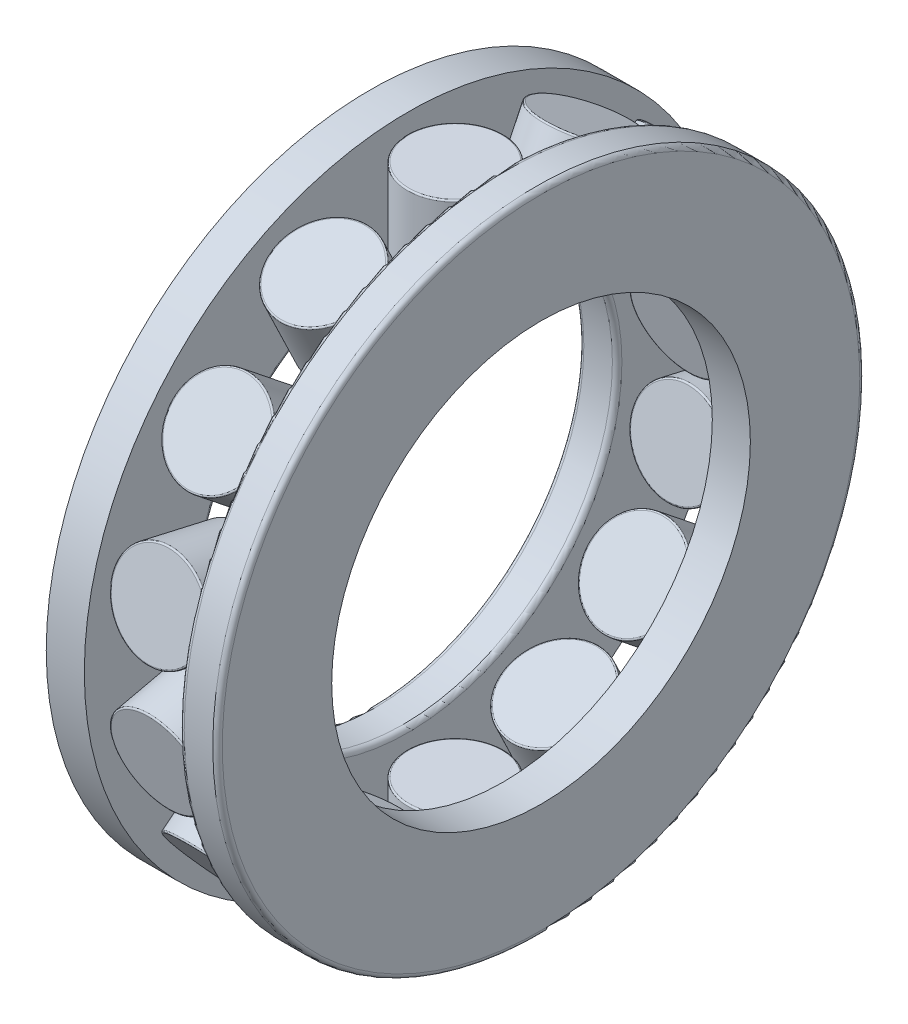
SolidWorks part; units mm, degrees
ref_plane "Plane1" through (0, 0, 0) normal (0, 0, 1) x (1, 0, 0)
ref_plane "Plane2" through (0, 0, 0) normal (0, 1, 0) x (1, 0, 0)
ref_plane "Plane3" through (0, 0, 0) normal (1, 0, 0) x (0, 0, -1)
sketch "Clipboard" plane through (0, 0, 0) normal (0, 0, 1) x (1, 0, 0)
  line L0 (-10, 0) -> (10, 0) construction
  line L1 (0, 0) -> (21.6965, -5.4095)
  line L2 (0, 0) -> (27.3662, 35.0271)
  line L3 (0, 0) -> (13.7666, -17.6205)
  line L4 (0, 0) -> (-22.3471, -0.7804)
  dimension "BallCLRad" = 44.45
  dimension "Count" = 52
  dimension "Show_count" = 52
  dimension "Max_count" = 14
  dimension "Min_count" = 2
sketch "InnRacSke" plane through (0, 0, 0) normal (0, 0, 1) x (1, 0, 0)
  line L1 (-7.9375, 34.925) -> (-14.2875, 34.925)
  line L2 (-14.2875, 34.925) -> (-14.2875, 53.975)
  line L3 (-14.2875, 53.975) -> (-7.9375, 53.975)
  line L4 (-7.9375, 53.975) -> (-7.9375, 34.925)
  line L5 (-34.925, 0) -> (34.925, 0) construction
  line L6 (0, 0) -> (0, 25.4) construction
  dimension "ID" = 69.85
  dimension "OD" = 107.95
  dimension "Width" = 28.575
  dimension "gap" = 15.875
revolve "Race" add sketch "InnRacSke" angle 360 about L5
ref_axis "Axis1" through (-50, 0, 0) along (1, 0, 0)
sketch "RolDetSke" plane through (0, 0, 0) normal (0, 0, 1) x (1, 0, 0)
  line L0 (0, 33.02) -> (0, 55.88) construction
  line L3 (0, 50.8) -> (7.7232, 50.8)
  line L4 (0, 50.8) -> (0, 38.1)
  line L5 (0, 38.1) -> (7.7232, 38.1)
  line L6 (7.9772, 50.546) -> (7.9772, 38.354)
  arc A0 (7.9772, 38.354) -> (7.7232, 38.1) centre (7.7232, 38.354) cw
  arc A1 (7.7232, 50.8) -> (7.9772, 50.546) centre (7.7232, 50.546) cw
  dimension "D1" = 0.254
  dimension "Roller_diameter" = 15.9544
  dimension "Cyl_Len" = 12.7
  dimension "offset" = 38.1
revolve "RollerDetailed" add sketch "RolDetSke" angle 360 about L0
sketch "RolSimSke" plane through (0, 0, 0) normal (0, 0, 1) x (1, 0, 0)
  line L1 (-17.78, 0) -> (12.7, 0) construction
  line L3 (-7.7232, 50.8) -> (7.7232, 50.8)
  line L4 (-7.9772, 50.546) -> (-7.9772, 38.354)
  line L5 (-7.7232, 38.1) -> (7.7232, 38.1)
  line L6 (7.9772, 50.546) -> (7.9772, 38.354)
  arc A0 (-7.9772, 38.354) -> (-7.7232, 38.1) centre (-7.7232, 38.354) ccw
  arc A1 (-7.7232, 50.8) -> (-7.9772, 50.546) centre (-7.7232, 50.546) ccw
  arc A2 (7.9772, 50.546) -> (7.7232, 50.8) centre (7.7232, 50.546) ccw
  arc A3 (7.7232, 38.1) -> (7.9772, 38.354) centre (7.7232, 38.354) ccw
  dimension "Roller_diameter" = 15.9544
  dimension "Cyl_Len" = 12.7
  dimension "offset" = 38.1
  dimension "Rol_rad" = 0.254
  dimension "Halfdia" = 7.9772
revolve "RollersSimplified" [suppressed] add sketch "RolSimSke" angle 360 about L1
mirror "Mirror1" about plane through (0, 0, 0) normal (1, 0, 0) of "Race"
fillet "Fillet" radius 0.7937 4 edges at (14.2875, 0, -53.975) (7.9375, 0, -53.975) (-14.2875, 0, -34.925) (-7.9375, 0, -34.925)
pattern_circular "RollersDetailed" count 14 every 25.714 about axis through (-50, 0, 0) along (1, 0, 0) of "RollerDetailed"
sketch "CagSpiSke" plane through (0, 0, 0) normal (0, 0, 1) x (1, 0, 0)
  line L0 (2.3932, 35.6235) -> (2.3932, 52.8955)
  line L1 (2.3932, 52.8955) -> (-2.3932, 52.8955)
  line L2 (-2.3932, 35.6235) -> (-2.3932, 52.8955)
  line L3 (-2.3932, 35.6235) -> (2.3932, 35.6235)
  line L4 (-34.925, 0) -> (34.925, 0) construction
  line L5 (0, 0) -> (0, 55.5677) construction
  dimension "ID" = 71.247
  dimension "OD" = 105.791
  dimension "Thickness" = 4.7863
revolve "CageSpine" [suppressed] add sketch "CagSpiSke" angle 360 about L4
equation "\"BallCLRad@Clipboard\" =  ( \"OD@InnRacSke\" + \"ID@InnRacSke\" )  / 4"
equation "\"offset@RolDetSke\" = \"BallCLRad@Clipboard\" - \"Cyl_Len@RolDetSke\" / 2"
equation "\"Roller_diameter@RolDetSke\" = \"gap@InnRacSke\" * 1.005"
equation "\"Cyl_Len@RolSimSke\" = \"Cyl_Len@RolDetSke\""
equation "\"offset@RolSimSke\" = \"BallCLRad@Clipboard\" - \"Cyl_Len@RolSimSke\" / 2"
equation "\"Roller_diameter@RolSimSke\" = \"Roller_diameter@RolDetSke\""
equation "\"Halfdia@RolSimSke\" = \"Roller_diameter@RolSimSke\" / 2"
equation "\"Max_count@Clipboard\" = int( 3.14159265 / atn(( \"Roller_diameter@RolDetSke\" / 2) / sqr( \"offset@RolDetSke\"  *  \"offset@RolDetSke\" - ( \"Roller_diameter@RolDetSke\" / 2) *  ( \"Roller_diameter@RolDetSke\" / 2))))"
equation "\"Max_count@Clipboard\" = ((sgn( \"Max_count@Clipboard\" - \"Count@Clipboard\" )-1)*( \"Max_count@Clipboard\" - \"Count@Clipboard\" ))/-2+ \"Count@Clipboard\""
equation "\"Count@RollersDetailed\" = int( \"Show_count@Clipboard\" ) "
equation "\"Count@RollersDetailed\" = ((sgn( \"Count@RollersDetailed\" - \"Max_count@Clipboard\" )-1)*( \"Count@RollersDetailed\" - \"Max_count@Clipboard\" ))/-2+ \"Max_count@Clipboard\""
equation "\"Count@RollersDetailed\" = ((sgn( \"Count@RollersDetailed\" - \"Min_count@Clipboard\" )+1)*( \"Count@RollersDetailed\" - \"Min_count@Clipboard\"))/2 +\"Min_count@Clipboard\""
equation "\"Angle@RollersDetailed\" = 360.0 / \"Max_count@Clipboard\""
equation "\"Angle@CageSpine\" =  \"Angle@RollersDetailed\" * ( \"Count@RollersDetailed\" -1 + int( \"Count@RollersDetailed\" / \"Max_count@Clipboard\" ) )  + 0.001 -  int( \"Count@RollersDetailed\" / \"Max_count@Clipboard\" ) * 0.001"
equation "\"Angle@CageSpine\" =  \"Angle@CageSpine\" * int( \"Min_count@Clipboard\" / 2) + int(1 / \"Min_count@Clipboard\")  * 0.001"
equation "\"Thickness@CagSpiSke\" =  \"Roller_diameter@RolDetSke\" * 0.3"
equation "\"OD@CagSpiSke\" = \"OD@InnRacSke\" * 0.98"
equation "\"ID@CagSpiSke\" =  \"ID@InnRacSke\" * 1.02"
